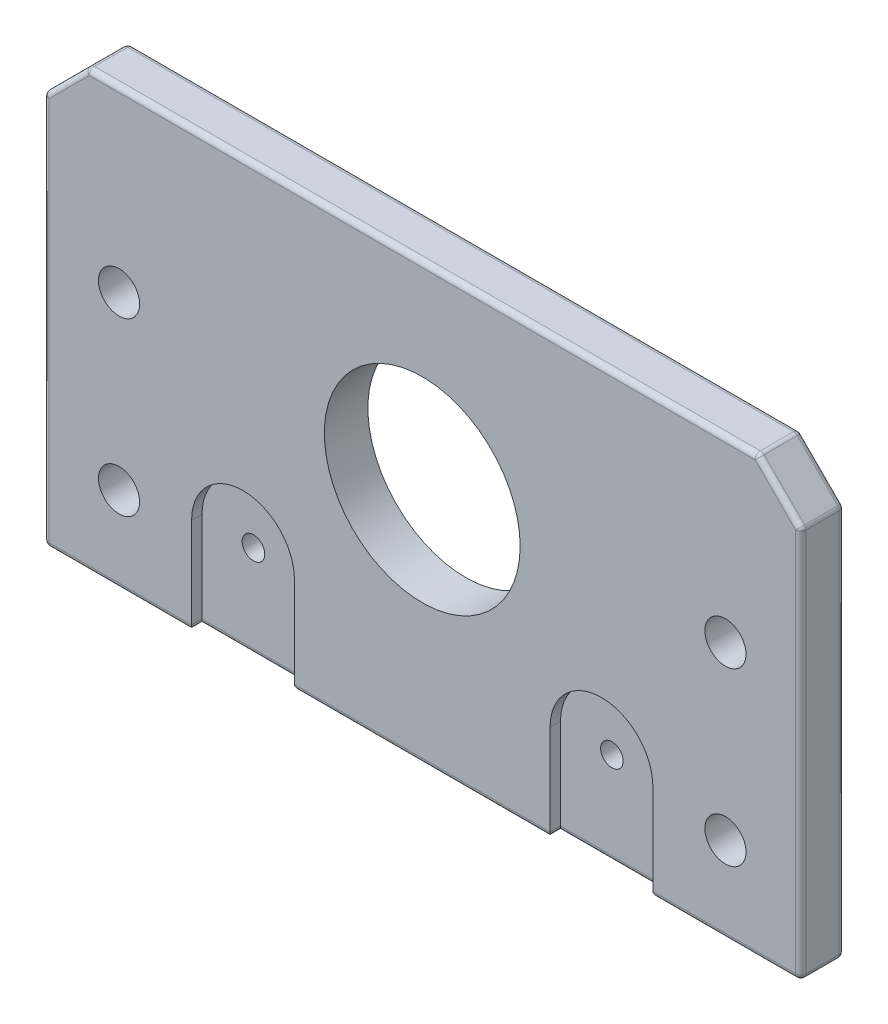
SolidWorks part; units mm, degrees
ref_plane "Front Plane" through (0, 0, 0) normal (0, 0, 1) x (1, 0, 0)
ref_plane "Top Plane" through (0, 0, 0) normal (0, 1, 0) x (1, 0, 0)
ref_plane "Right Plane" through (0, 0, 0) normal (1, 0, 0) x (0, 0, -1)
sketch "Sketch2" plane through (0, 0, 0) normal (0, 1, 0) x (1, 0, 0)
  line L1 (-55.245, 3.175) -> (55.245, 3.175)
  line L2 (-55.245, 3.175) -> (-55.245, -3.175)
  line L3 (-55.245, -3.175) -> (55.245, -3.175)
  line L4 (55.245, 3.175) -> (55.245, -3.175)
  point P4 (0, 3.175)
  point P7 (-55.245, 0)
  dimension "D1" = 6.35
  dimension "D2" = 110.49
extrude "Boss-Extrude1" add sketch "Sketch2" against normal blind 63.5
sketch "Sketch3" plane through (0, 0, 3.175) normal (0, 0, 1) x (1, 0, 0)
  line L2 (-55.245, 0) -> (55.245, 0) construction
  circle A0 centre (0, -28.815) radius 14.2875
  point P2 (0, 0)
  dimension "D1" = 28.815
  dimension "D3" = 28.575
extrude "Cut-Extrude1" cut sketch "Sketch3" against normal through all
chamfer "Chamfer1" distance 6.35 angle 45 2 edges at (-55.245, 0, 0) (55.245, 0, 0)
fillet "Fillet1" [suppressed] radius 0.762
hole_wizard "CBORE for M4 SHCS2" [suppressed] positions "Sketch9" profile "Sketch10" counterbore size "M4" standard "ANSI Metric"
sketch "Sketch9" [suppressed] plane through (0, 0, 3.175) normal (0, 0, 1) x (1, 0, 0)
  line L0 (-48.5794, 0) -> (48.5794, 0) construction
  line L1 (-55.245, -62.738) -> (-55.245, -6.6656) construction
  point P0 (-17.9605, -10.8545)
  dimension "D1" = 10.8545
  dimension "D2" = 37.2845
sketch "Sketch10" plane through (-17.9605, -10.8545, 3.175) normal (1, 0, 0) x (0, -1, 0)
  line L0 (0, 0) -> (0, 6.35)
  line L1 (0, 6.35) -> (2.25, 6.35)
  line L3 (2.25, 6.35) -> (2.25, 4)
  line L4 (2.25, 4) -> (4, 4)
  line L5 (4, 4) -> (4, 0)
  line L7 (4, 0) -> (0, 0)
  line L11 (0, -6.35) -> (0, 107.95) construction
  dimension "Thru Hole Dia." = 4.5
  dimension "Thru Hole Depth" = 6.35
  dimension "C'Bore Dia." = 8
  dimension "C'Bore Depth" = 4
sketch "Sketch12" plane through (0, 0, 3.175) normal (0, 0, 1) x (1, 0, 0)
  line L0 (-33.655, -49.5) -> (-33.655, -63.5)
  line L1 (-55.245, -63.5) -> (-55.245, -6.35) construction
  line L2 (-33.655, -63.5) -> (-18.655, -63.5)
  line L3 (-55.245, -63.5) -> (55.245, -63.5) construction
  line L5 (-18.655, -63.5) -> (-18.655, -49.5)
  arc A0 (-18.655, -49.5) -> (-33.655, -49.5) centre (-26.155, -49.5) ccw
  dimension "D4" = 7.5
  dimension "D1" = 14
  dimension "D2" = 15
  dimension "D3" = 14
  dimension "D5" = 29.09
extrude "Cut-Extrude2" cut sketch "Sketch12" against normal blind 1.524
mirror "Mirror1" about plane through (0, 0, 0) normal (1, 0, 0) of "Cut-Extrude2"
hole_wizard "Tap Drill for M4x0.7 Tap1" positions "Sketch13" profile "Sketch14" hole size "M4x0.7" standard "ANSI Metric" end condition through all
sketch "Sketch13" plane through (0, 0, 3.175) normal (0, 0, 1) x (1, 0, 0)
  line L1 (0, -3.4925) -> (0, 3.4925) construction
  line L2 (-48.895, 0) -> (48.895, 0) construction
  point P0 (-26.155, -50)
  point P3 (26.155, -50)
  dimension "D1" = 52.31
  dimension "D2" = 26.155
  dimension "D3" = 50
sketch "Sketch14" plane through (-26.155, -50, 3.175) normal (1, 0, 0) x (0, -1, 0)
  line L0 (0, 0) -> (0, 6.35)
  line L1 (0, 6.35) -> (1.65, 6.35)
  line L2 (1.65, 6.35) -> (1.65, 0)
  line L5 (1.65, 0) -> (0, 0)
  line L11 (0, -6.35) -> (0, 107.95) construction
  dimension "Thru Hole Dia." = 3.3
  dimension "Thru Hole Depth" = 6.35
hole_wizard "Tap Drill for M7x1.0 Tap1" positions "Sketch17" profile "Sketch16" hole size "M7x1.0" standard "ANSI Metric" end condition through all
sketch "Sketch17" plane through (0, 0, -3.175) normal (0, 0, -1) x (-1, 0, 0)
  line L0 (0, 3.4925) -> (0, -3.4925) construction
  line L1 (-48.895, 0) -> (48.895, 0) construction
  point P0 (44.245, -26)
  point P3 (44.245, -51)
  point P6 (-44.245, -51)
  point P9 (-44.245, -26)
  dimension "D1" = 25
  dimension "D2" = 25
  dimension "D3" = 88.49
  dimension "D4" = 44.245
  dimension "D5" = 26
sketch "Sketch16" plane through (-44.245, -26, -3.175) normal (1, 0, 0) x (0, 1, 0)
  line L0 (0, 0) -> (0, 6.35)
  line L1 (0, 6.35) -> (3, 6.35)
  line L2 (3, 6.35) -> (3, 0)
  line L5 (3, 0) -> (0, 0)
  line L11 (0, -6.35) -> (0, 107.95) construction
  dimension "Thru Hole Dia." = 6
  dimension "Thru Hole Depth" = 6.35
fillet "Fillet2" radius 0.762 26 edges at (44.45, -63.5, 3.175) (0, -63.5, -3.175) (-44.45, -63.5, 3.175) (-33.655, -63.5, 2.413) (-26.155, -63.5, 1.651) (-18.655, -63.5, 2.413) (0, -63.5, 3.175) (18.655, -63.5, 2.413) (26.155, -63.5, 1.651) (33.655, -63.5, 2.413) (55.245, -63.5, 0) (55.245, -34.925, 3.175) (55.245, -34.925, -3.175) (52.07, -3.175, -3.175) (55.245, -6.35, 0) (52.07, -3.175, 3.175) (48.895, 0, 0) (0, 0, 3.175) (0, 0, -3.175) (-48.895, 0, 0) (-52.07, -3.175, 3.175) (-52.07, -3.175, -3.175) (-55.245, -63.5, 0) (-55.245, -34.925, -3.175) (-55.245, -6.35, 0) (-55.245, -34.925, 3.175)
